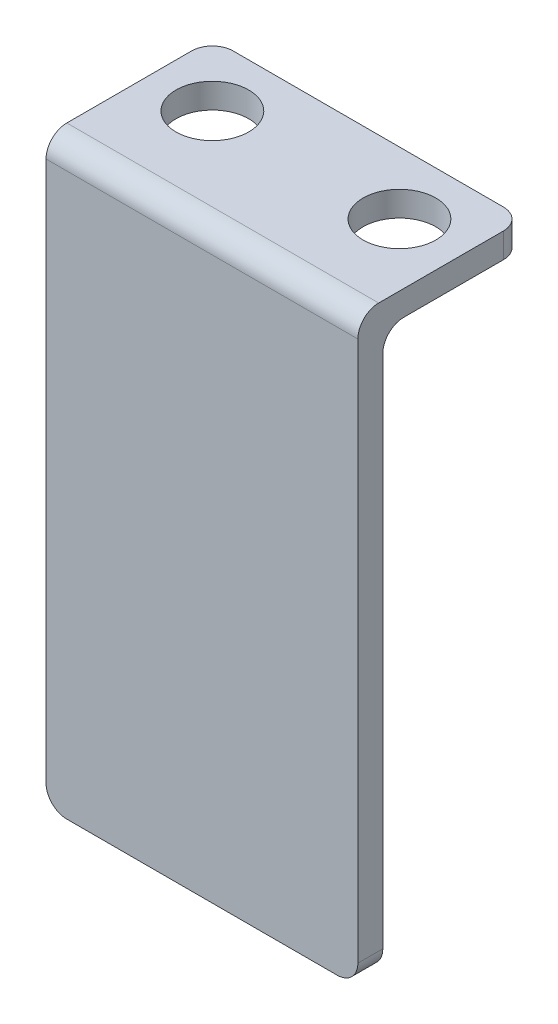
SolidWorks part; units mm, degrees
ref_plane "前视基准面" through (0, 0, 0) normal (0, 0, 1) x (1, 0, 0)
ref_plane "上视基准面" through (0, 0, 0) normal (0, 1, 0) x (1, 0, 0)
ref_plane "右视基准面" through (0, 0, 0) normal (1, 0, 0) x (0, 0, -1)
sketch "草图5" plane through (0, 0, 0) normal (1, 0, 0) x (0, 0, -1)
  line L0 (0, -28) -> (0, 0)
  line L1 (0, 0) -> (8, 0)
  dimension "D1" = 8
  dimension "D2" = 28
extrude "拉伸-薄壁1" add sketch "草图5" along normal blind 15 thin
hole_wizard "Ø3.5 (3.5) 直径孔1" positions "草图4" profile "草图3" hole size "Ø3.5" standard "GB"
sketch "草图4" plane through (4.3054, 0, -7.2198) normal (0, -1, 0) x (1, 0, 0)
  line L2 (10.6946, -0.7802) -> (-4.3054, -0.7802) construction
  line L3 (10.6946, 6.0198) -> (10.6946, -0.7802) construction
  line L4 (3.1946, -0.7802) -> (3.1946, -0.6917) construction
  point P0 (7.6946, 2.2198)
  point P12 (10.6946, 2.6198)
  point P18 (-1.3054, 2.2198)
  dimension "D1" = 3
  dimension "D2" = 3
sketch "草图3" plane through (12, 0, -5) normal (1, 0, 0) x (0, 0, 1)
  line L0 (0, 0) -> (0, 4)
  line L1 (0, 4) -> (1.75, 4)
  line L2 (1.75, 4) -> (1.75, 0)
  line L5 (1.75, 0) -> (0, 0)
  line L10 (0, 4) -> (-1.75, 4) construction
  line L11 (0, -6.35) -> (0, 107.95) construction
  dimension "孔直径" = 3.5
  dimension "孔深度" = 4
  dimension "导头角度" = 180
fillet "圆角1" radius 1 4 edges at (0, -28, -0.6) (15, -28, -0.6) (0, -0.6, -8) (15, -0.6, -8)
fillet "圆角2" radius 1 2 edges at (7.5, -1.2, -1.2) (7.5, 0, 0)
